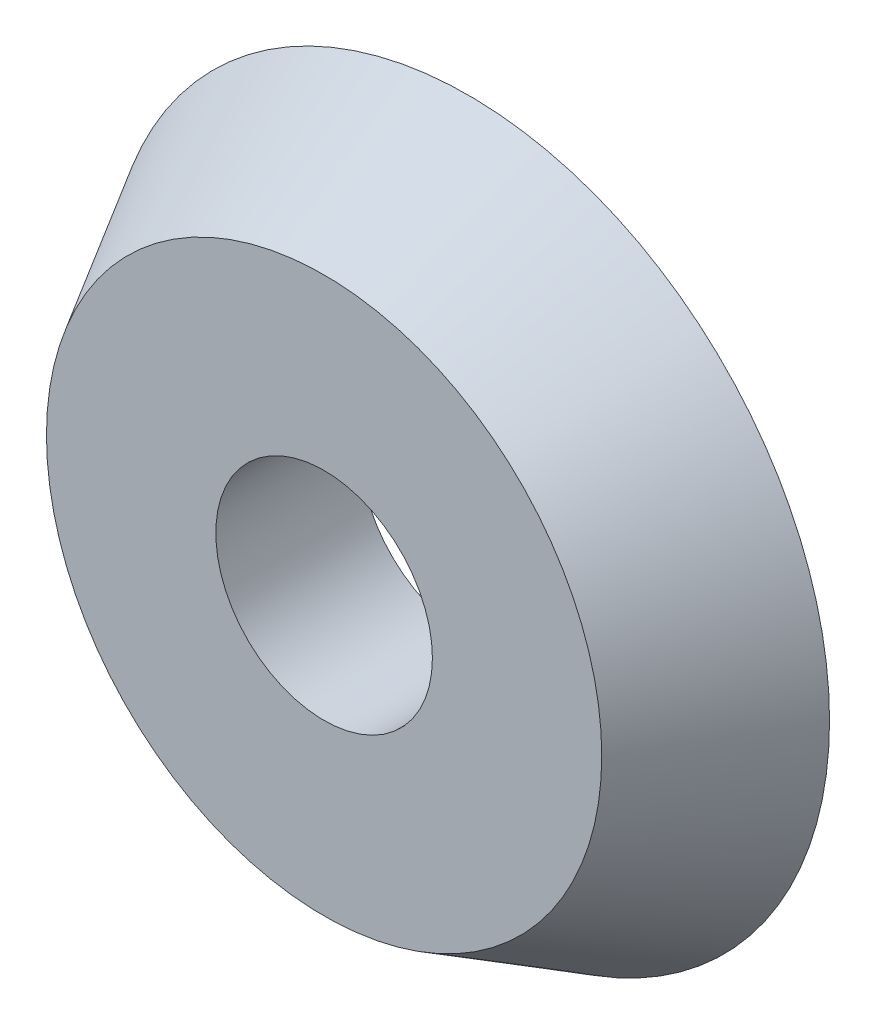
SolidWorks part; units mm, degrees
ref_plane "Front Plane" through (0, 0, 0) normal (1, 0, 0) x (0, 1, 0)
ref_plane "Top Plane" through (0, 0, 0) normal (0, 0, 1) x (0, 1, 0)
ref_plane "Right Plane" through (0, 0, 0) normal (0, 1, 0) x (-1, 0, 0)
sketch "Sketch1" plane through (0, 0, 0) normal (0, 0, 1) x (0, 1, 0)
  circle A1 centre (0, 0) radius 50
  dimension "D1" = 100
extrude "Boss-Extrude1" add sketch "Sketch1" along normal blind 20 draft 30
sketch "Sketch3" plane through (0, 0, 20) normal (0, 0, 1) x (1, 0, 0)
  circle A0 centre (0, 0) radius 15
  dimension "D1" = 30
extrude "Cut-Extrude2" cut sketch "Sketch3" against normal through all
